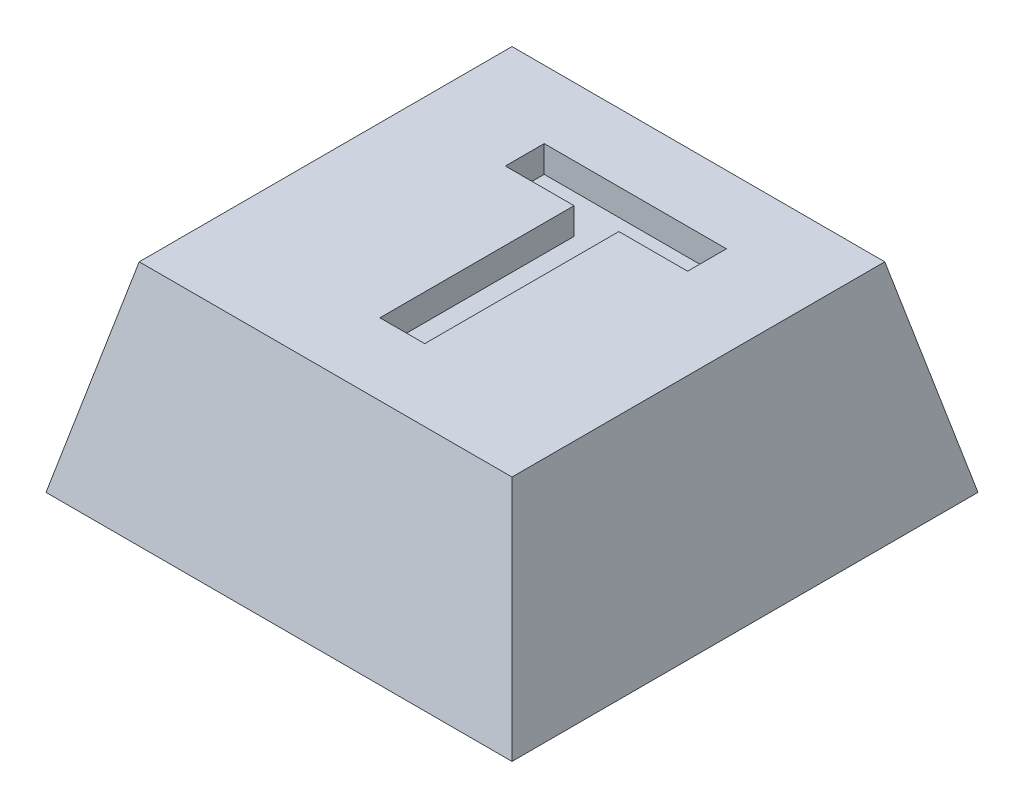
SolidWorks part; units mm, degrees
ref_plane "Front Plane" through (0, 0, 0) normal (0, 0, 1) x (1, 0, 0)
ref_plane "Top Plane" through (0, 0, 0) normal (0, 1, 0) x (1, 0, 0)
ref_plane "Right Plane" through (0, 0, 0) normal (1, 0, 0) x (0, 0, -1)
sketch "Sketch1" plane through (0, 0, 0) normal (0, 1, 0) x (1, 0, 0)
  line L1 (0, 0) -> (7, 0)
  line L2 (0, 0) -> (0, 7)
  line L3 (0, 7) -> (7, 7)
  line L4 (7, 0) -> (7, 7)
  dimension "D1" = 7
  dimension "D2" = 7
extrude "Boss-Extrude1" add sketch "Sketch1" along normal blind 3
sketch "Sketch2" plane through (0, 0, 0) normal (0, 0, 1) x (1, 0, 0)
  line L0 (0, 0) -> (0.7, 3)
  line L1 (0, 3) -> (7, 3) construction
  line L2 (0.7, 3) -> (0, 3)
  line L3 (0, 3) -> (0, 0)
  line L4 (7, 0) -> (6.3, 3)
  line L5 (6.3, 3) -> (7, 3)
  line L6 (7, 3) -> (7, 0)
  dimension "D1" = 0.7
  dimension "D2" = 0.7
extrude "Cut-Extrude1" cut sketch "Sketch2" against normal blind 7
sketch "Sketch3" plane through (0, 0, 0) normal (1, 0, 0) x (0, 0, -1)
  line L0 (0, 0) -> (0.7, 3)
  line L1 (7, 3) -> (0, 3) construction
  line L2 (0.7, 3) -> (0, 3)
  line L3 (0, 3) -> (0, 0)
  line L4 (7, 3) -> (6.3, 3)
  line L5 (6.3, 3) -> (7, 0)
  line L6 (7, 3) -> (7, 0)
  dimension "D1" = 0.7
  dimension "D2" = 0.7
extrude "Cut-Extrude2" cut sketch "Sketch3" along normal blind 11
sketch "Sketch4" plane through (0, 0, 0) normal (0, -1, 0) x (1, 0, 0)
  line L0 (3.5, 0) -> (3.5, -7) construction
  line L1 (0, 0) -> (7, 0) construction
  line L2 (7, -7) -> (0, -7) construction
  line L3 (0, -3.5) -> (7, -3.5) construction
  line L4 (0, -7) -> (0, 0) construction
  line L5 (7, 0) -> (7, -7) construction
  circle A0 centre (3.5, -3.5) radius 1.8
  dimension "D1" = 3.6
extrude "Cut-Extrude3" cut sketch "Sketch4" against normal blind 0.8
sketch "Sketch5" plane through (0, 3, 0) normal (0, 1, 0) x (1, 0, 0)
  text T0 "T" font "Arial" height 3.5
extrude "Cut-Extrude4" cut sketch "Sketch5" against normal blind 0.4
